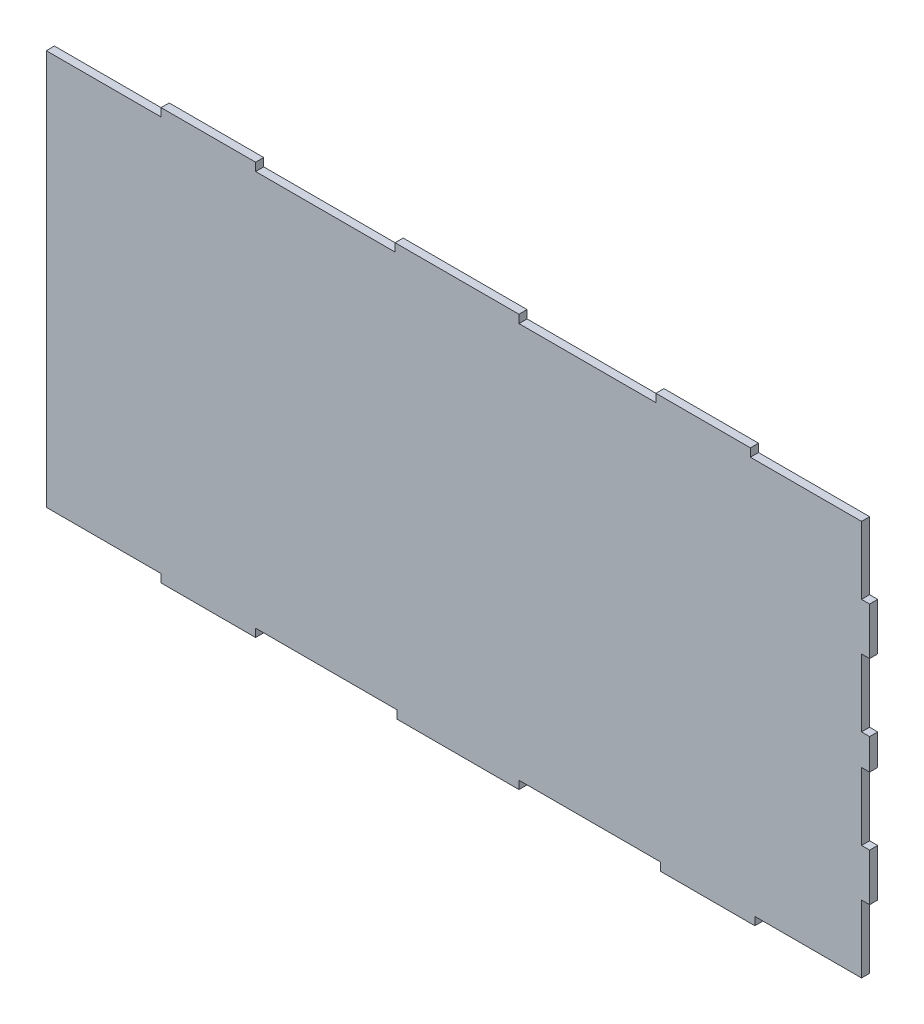
SolidWorks part; units mm, degrees
ref_plane "Front Plane" through (0, 0, 0) normal (1, 0, 0) x (0, 1, 0)
ref_plane "Top Plane" through (0, 0, 0) normal (0, 0, 1) x (0, 1, 0)
ref_plane "Right Plane" through (0, 0, 0) normal (0, 1, 0) x (-1, 0, 0)
sketch "Sketch1" plane through (0, 0, 0) normal (0, 0, 1) x (0, 1, 0)
  line L0 (-146.4, 234.8) -> (-146.4, 304.8)
  line L1 (-146.4, 304.8) -> (-76.4, 304.8)
  line L2 (76.4, 304.8) -> (146.4, 304.8)
  line L3 (146.4, 304.8) -> (146.4, 234.8)
  line L4 (-146.4, -298.8) -> (-96.4, -298.8)
  line L8 (-96.4, -298.8) -> (-96.4, -304.8)
  line L9 (-76.4, 304.8) -> (76.4, 304.8)
  line L10 (146.4, 234.8) -> (146.4, 219.8)
  line L11 (146.4, 219.8) -> (152.4, 219.8)
  line L12 (152.4, 219.8) -> (152.4, 149.8)
  line L13 (152.4, 149.8) -> (146.4, 149.8)
  line L14 (146.4, 149.8) -> (146.4, 46.5642)
  line L15 (146.4, 46.5642) -> (152.4, 46.5642)
  line L16 (152.4, 46.5642) -> (152.4, -45.2)
  line L17 (152.4, -45.2) -> (146.4, -45.2)
  line L18 (146.4, -45.2) -> (146.4, -146.5366)
  line L19 (146.4, -146.5366) -> (152.4, -146.5366)
  line L20 (152.4, -146.5366) -> (152.4, -216.5366)
  line L21 (152.4, -216.5366) -> (146.4, -216.5366)
  line L22 (146.4, -216.5366) -> (146.4, -298.8)
  line L23 (96.4, -304.8) -> (61.4, -304.8)
  line L24 (-146.4, -298.8) -> (-146.4, -219.8)
  line L25 (-146.4, -219.8) -> (-152.4, -219.8)
  line L26 (-152.4, -219.8) -> (-152.4, -149.8)
  line L27 (-152.4, -149.8) -> (-146.4, -149.8)
  line L28 (-146.4, -149.8) -> (-146.4, -45.2)
  line L29 (-146.4, -45.2) -> (-152.4, -45.2)
  line L30 (-152.4, -45.2) -> (-152.4, 45.2)
  line L31 (-152.4, 45.2) -> (-146.4, 45.2)
  line L32 (-146.4, 45.2) -> (-146.4, 149.8)
  line L33 (-146.4, 149.8) -> (-152.4, 149.8)
  line L34 (-152.4, 149.8) -> (-152.4, 219.8)
  line L35 (-152.4, 219.8) -> (-146.4, 219.8)
  line L36 (-146.4, 219.8) -> (-146.4, 234.8)
  line L37 (-61.4, -304.8) -> (-61.4, -298.8)
  line L38 (-61.4, -298.8) -> (-11.4, -298.8)
  line L39 (-11.4, -298.8) -> (-11.4, -304.8)
  line L40 (11.4, -304.8) -> (11.4, -298.8)
  line L41 (11.4, -298.8) -> (61.4, -298.8)
  line L42 (61.4, -298.8) -> (61.4, -304.8)
  line L43 (96.4, -304.8) -> (96.4, -298.8)
  line L44 (96.4, -298.8) -> (146.4, -298.8)
  line L45 (-61.4, -304.8) -> (-96.4, -304.8)
  line L46 (11.4, -304.8) -> (-11.4, -304.8)
  point P27 (-618.4945, -136.583)
  dimension "D2" = 50
  dimension "D3" = 50
  dimension "D4" = 50
  dimension "D5" = 35
  dimension "D6" = 50
  dimension "D7" = 35
  dimension "D8" = 6
  dimension "D9" = 609.6
extrude "Boss-Extrude1" add sketch "Sketch1" along normal blind 6
